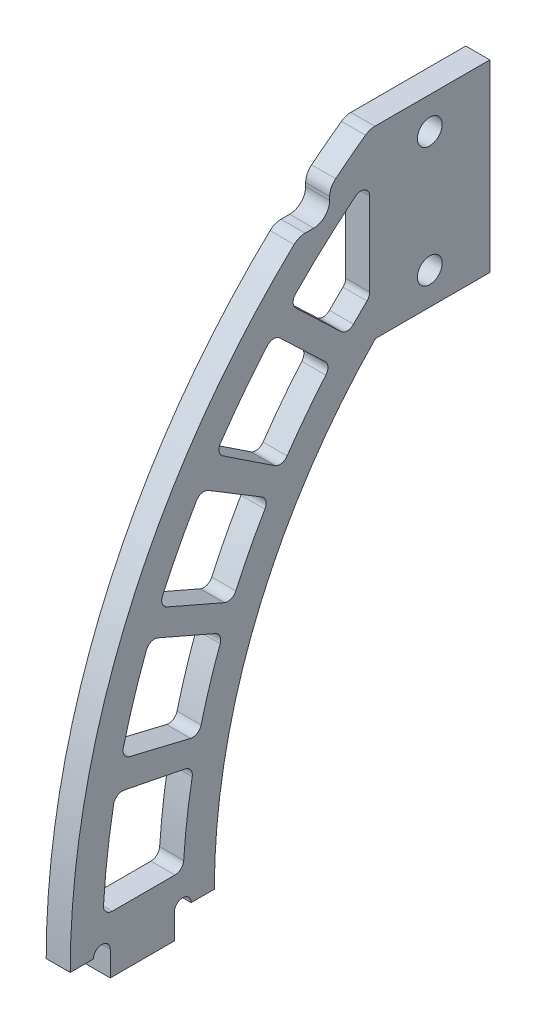
SolidWorks part; units mm, degrees
material "环氧树脂板"
ref_plane "前视基准面" through (0, 0, 0) normal (0, 0, 1) x (1, 0, 0)
ref_plane "上视基准面" through (0, 0, 0) normal (0, 1, 0) x (1, 0, 0)
ref_plane "右视基准面" through (0, 0, 0) normal (1, 0, 0) x (0, 0, -1)
sketch "草图1" plane through (0, 0, 0) normal (1, 0, 0) x (0, 0, -1)
  line L0 (-39.9, -68.5) -> (-44.9, -68.5)
  line L1 (-31.9, -71.6) -> (-39.9, -71.6)
  line L2 (-31.9, -71.6) -> (-31.9, -68.5)
  line L3 (-31.9, -68.5) -> (-39.9, -68.5) construction
  line L4 (-39.9, -71.6) -> (-39.9, -68.5)
  line L5 (-31.9, -71.6) -> (-39.9, -68.5) construction
  line L6 (-31.9, -68.5) -> (-39.9, -71.6) construction
  line L7 (-31.9, -68.5) -> (-26.9, -68.5)
  line L8 (-7.5, 4) -> (7.5, 4)
  line L9 (7.5, 4) -> (7.5, -19)
  line L10 (7.5, -19) -> (-6.7878, -19)
  line L11 (0, 0) -> (0, 4) construction
  line L12 (-40.8058, -64.5) -> (-30.7932, -64.5)
  line L13 (-7.5, -0.9686) -> (-7.5, -14.0843)
  line L14 (-10.2772, -16.8579) -> (-17.5264, -9.9696)
  line L15 (-12.3002, -19.074) -> (-19.5545, -12.1808)
  line L16 (-18.4191, -27.0798) -> (-26.7544, -21.555)
  line L17 (-20.0265, -29.6136) -> (-28.5762, -24.4267)
  line L18 (-24.6623, -38.5604) -> (-33.8303, -34.5668)
  line L19 (-25.8053, -41.3347) -> (-34.9798, -37.3384)
  line L20 (-7.5, -14.0843) -> (44.0707, -68.5) construction
  line L21 (-38.5392, -48.6097) -> (-28.817, -50.9506)
  line L22 (-39.269, -51.9314) -> (-29.4609, -53.8813)
  circle A0 centre (0, 0) radius 1.55
  circle A1 centre (0, -15) radius 1.55
  arc A2 (-7.5, 4) -> (-44.9, -68.5) centre (44.0707, -68.5) ccw
  circle A8 centre (-40.95, -68.5) radius 1.05
  circle A9 centre (-30.85, -68.5) radius 1.05
  arc A10 (-6.7878, -19) -> (-26.9, -68.5) centre (44.0707, -68.5) ccw
  arc A11 (-7.5, -0.9686) -> (-17.5264, -9.9696) centre (44.0707, -68.5) ccw
  arc A12 (-7.5, -14.0843) -> (-10.2772, -16.8579) centre (44.0707, -68.5) ccw
  arc A13 (-34.9798, -37.3384) -> (-38.5392, -48.6097) centre (44.0707, -68.5) ccw
  arc A14 (-25.8053, -41.3347) -> (-28.817, -50.9506) centre (44.0707, -68.5) ccw
  arc A15 (-39.269, -51.9314) -> (-40.8058, -64.5) centre (44.0707, -68.5) ccw
  arc A16 (-29.4609, -53.8813) -> (-30.7932, -64.5) centre (44.0707, -68.5) ccw
  arc A17 (-28.5762, -24.4267) -> (-33.8303, -34.5668) centre (44.0707, -68.5) ccw
  arc A18 (-20.0265, -29.6136) -> (-24.6623, -38.5604) centre (44.0707, -68.5) ccw
  arc A19 (-19.5545, -12.1808) -> (-26.7544, -21.555) centre (44.0707, -68.5) ccw
  arc A20 (-12.3002, -19.074) -> (-18.4191, -27.0798) centre (44.0707, -68.5) ccw
  point P7 (-35.9, -70.05)
  point P43 (-13.9018, -13.4137)
  dimension "D1" = 3.1
  dimension "D7" = 5
  dimension "D8" = 15
  dimension "D9" = 2.1
  dimension "D15" = 4
  dimension "D16" = 4
  dimension "D2" = 15
  dimension "D3" = 35.9
  dimension "D4" = 8
  dimension "D5" = 3.1
  dimension "D6" = 55.05
  dimension "D10" = 5
  dimension "D11" = 4
  dimension "D12" = 4
  dimension "D13" = 4
  dimension "D14" = 7.5
  dimension "D17" = 3
  dimension "D18" = 3
  dimension "D19" = 10
  dimension "D20" = 3
  dimension "D21" = 3
  dimension "D22" = 10
  dimension "D23" = 3
  dimension "D24" = 10
extrude "凸台-拉伸1" add sketch "草图1" along normal blind 3
fillet "圆角1" radius 1.1 20 edges at (1.5, -12.1808, 19.5545) (1.5, -21.555, 26.7544) (1.5, -27.0798, 18.4191) (1.5, -19.074, 12.3002) (1.5, -24.4267, 28.5762) (1.5, -34.5668, 33.8303) (1.5, -38.5604, 24.6623) (1.5, -29.6136, 20.0265) (1.5, -51.9314, 39.269) (1.5, -64.5, 40.8058) (1.5, -64.5, 30.7932) (1.5, -53.8813, 29.4609) (1.5, -37.3384, 34.9798) (1.5, -48.6097, 38.5392) (1.5, -50.9506, 28.817) (1.5, -41.3347, 25.8053) (1.5, -16.8579, 10.2772) (1.5, -14.0843, 7.5) (1.5, -9.9696, 17.5264) (1.5, -0.9686, 7.5)
sketch "草图2" plane through (3, 0, 0) normal (1, 0, 0) x (0, 0, -1)
  line L0 (-12.5, 3.5475) -> (-12.5, -3.2)
  line L1 (-12.5, -3.2) -> (-18.4274, -3.2)
  line L2 (-18.4274, -3.2) -> (-18.4274, 3.5475)
  line L3 (-18.4274, 3.5475) -> (-12.5, 3.5475)
  dimension "D1" = 12.5
  dimension "D2" = 3.2
extrude "切除-拉伸1" cut sketch "草图2" against normal blind 10
fillet "圆角2" radius 2 4 edges at (1.5, 4, 7.5) (1.5, -3.2, 16.3586) (1.5, 0.1698, 12.5) (1.5, -3.2, 12.5)
